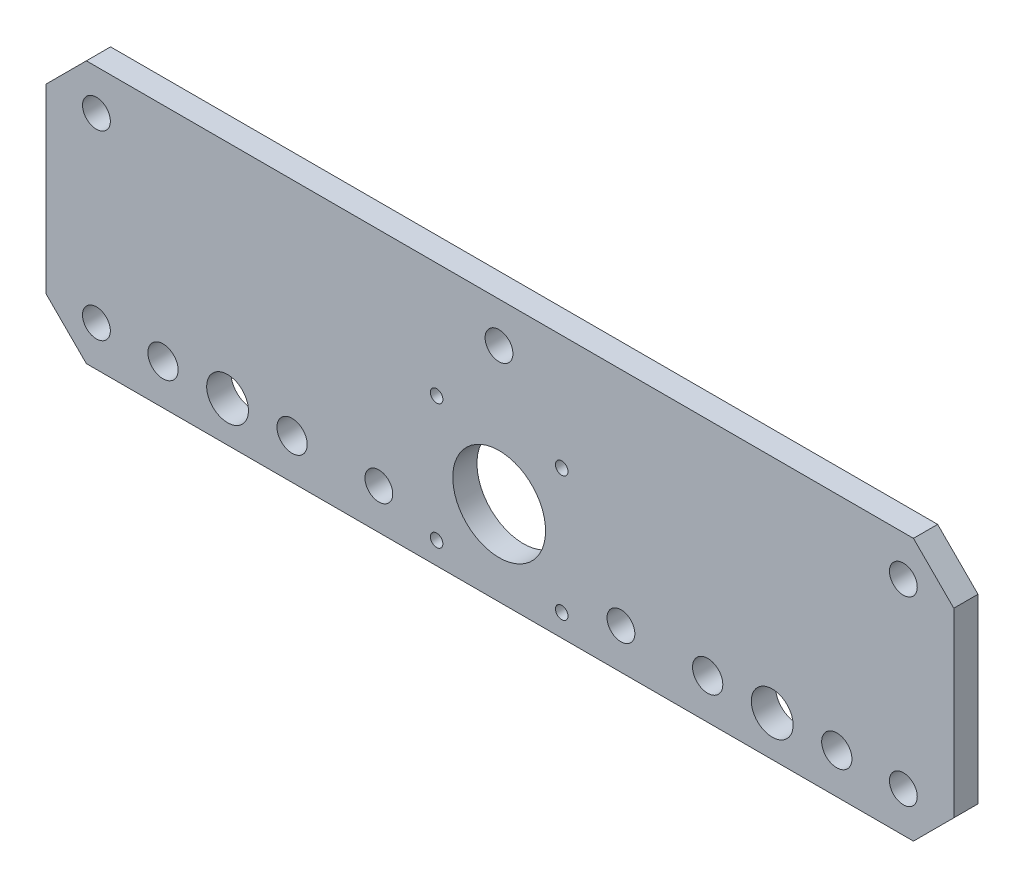
SolidWorks part; units mm, degrees
ref_plane "Front Plane" through (0, 0, 0) normal (0, 0, 1) x (1, 0, 0)
ref_plane "Top Plane" through (0, 0, 0) normal (0, 1, 0) x (1, 0, 0)
ref_plane "Right Plane" through (0, 0, 0) normal (1, 0, 0) x (0, 0, -1)
sketch "Sketch1" plane through (0, 0, 0) normal (0, 0, 1) x (1, 0, 0)
  line L0 (-112.5, -30.7797) -> (112.5, -30.7797)
  line L1 (112.5, -30.7797) -> (112.5, 34.2203)
  line L3 (112.5, 34.2203) -> (-112.5, 34.2203)
  line L5 (-112.5, 34.2203) -> (-112.5, -30.7797)
  line L6 (0, 34.2203) -> (0, -30.7797) construction
  circle A2 centre (83.5, -20.7797) radius 3.75
  circle A3 centre (51.5, -20.7797) radius 3.75
  circle A4 centre (67.5, -20.7797) radius 5.1773
  circle A5 centre (-51.5, -20.7797) radius 3.75
  circle A6 centre (-83.5, -20.7797) radius 3.75
  circle A7 centre (-67.5, -20.7797) radius 5.175
  circle A8 centre (30, -20.7797) radius 3.4458
  circle A9 centre (-30, -20.7797) radius 3.4458
  circle A10 centre (100, -20.7797) radius 3.4458
  circle A11 centre (100, 24.2203) radius 3.4458
  circle A12 centre (-0.2228, 24.2203) radius 3.4458
  circle A13 centre (-100, -20.7797) radius 3.4458
  circle A14 centre (-100, 24.2203) radius 3.4458
  point P1 (0, 34.2203)
  dimension "D6" = 10.35
  dimension "D7" = 10.3546
  dimension "D8" = 7.5
  dimension "D10" = 7.5
  dimension "D12" = 7.5
  dimension "D13" = 7.5
  dimension "D1" = 65
  dimension "D2" = 225
  dimension "D3" = 60
  dimension "D4" = 10
  dimension "D5" = 135
  dimension "D9" = 16
  dimension "D11" = 16
  dimension "D14" = 200
  dimension "D15" = 10
extrude "Boss-Extrude1" add sketch "Sketch1" along normal blind 6
chamfer "Chamfer1" distance 10 angle 45 4 edges at (112.5, -30.7797, 3) (112.5, 34.2203, 3) (-112.5, -30.7797, 3) (-112.5, 34.2203, 3)
sketch "Sketch3" plane through (0, 0, 6) normal (0, 0, 1) x (1, 0, 0)
  line L0 (-102.5, -30.7797) -> (102.5, -30.7797) construction
  circle A0 centre (-15.6808, -25.2797) radius 1.55
  circle A1 centre (-15.6808, 5.7203) radius 1.55
  circle A2 centre (15.3192, 5.7203) radius 1.55
  circle A3 centre (15.3192, -25.2797) radius 1.55
  circle A4 centre (-0.1808, -9.7797) radius 11.5
  dimension "D6" = 3.1
  dimension "D7" = 23
  dimension "D1" = 31
  dimension "D2" = 31
  dimension "D3" = 31
  dimension "D4" = 15.5
  dimension "D5" = 15.5
  dimension "D8" = 5.5
extrude "Cut-Extrude1" cut sketch "Sketch3" against normal up to next
